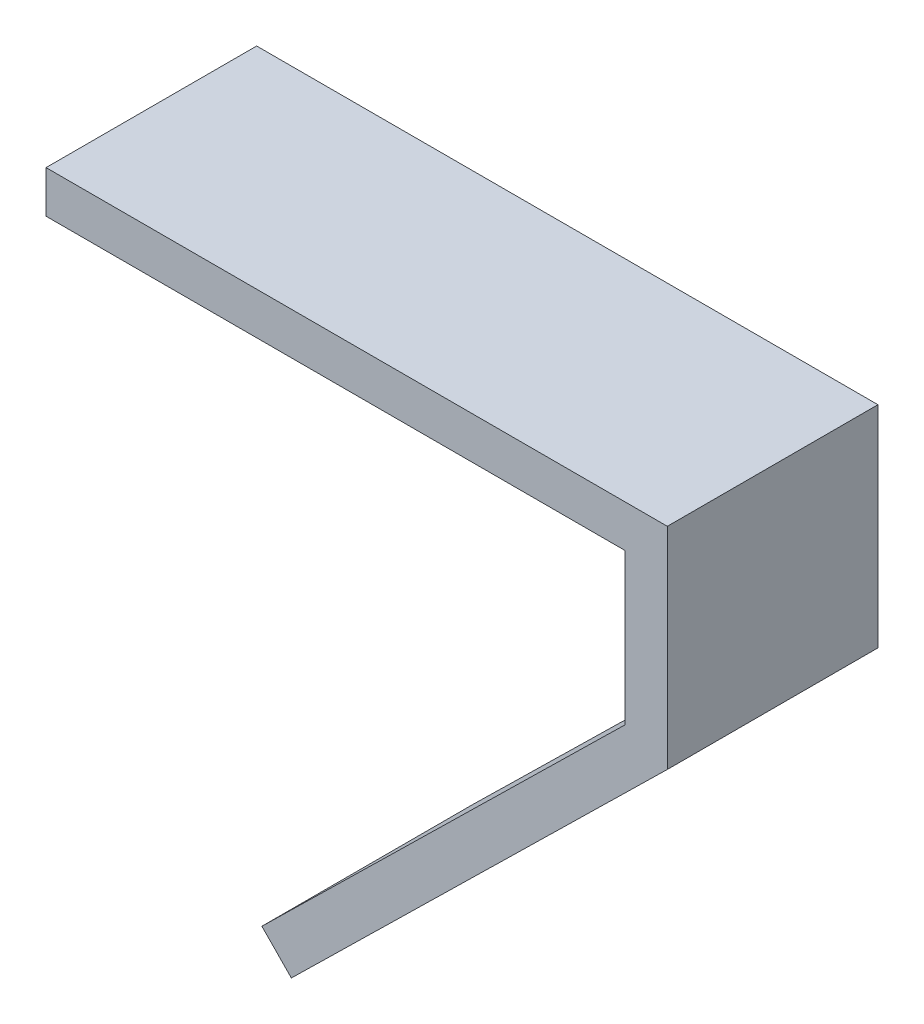
SolidWorks part; units mm, degrees
ref_plane "Front Plane" through (0, 0, 0) normal (0, 0, 1) x (1, 0, 0)
ref_plane "Top Plane" through (0, 0, 0) normal (0, 1, 0) x (1, 0, 0)
ref_plane "Right Plane" through (0, 0, 0) normal (1, 0, 0) x (0, 0, -1)
sketch "Sketch1" plane through (0, 0, 0) normal (0, 1, 0) x (1, 0, 0)
  line L0 (-86.6457, 0) -> (149.3256, 0) construction
  line L1 (-55, 0) -> (55, 0) construction
  line L2 (88.8579, 0) -> (88.8579, -74.8471) construction
ref_plane "Plane1" through (43.545, -44.4202, 0) normal (-0.7, 0.7141, 0) x (0, 0, 1)
sketch "Sketch2" plane through (43.545, -44.4202, 0) normal (-0.7, 0.7141, 0) x (0, 0, 1)
  line L1 (28.0347, 87.6783) -> (8.0347, 87.6783)
  line L2 (28.0347, 87.6783) -> (28.0347, 37.6783)
  line L3 (28.0347, 37.6783) -> (8.0347, 37.6783)
  line L4 (8.0347, 87.6783) -> (8.0347, 37.6783)
  line L5 (28.0347, 87.6783) -> (8.0347, 37.6783) construction
  line L6 (28.0347, 37.6783) -> (8.0347, 87.6783) construction
  point P0 (18.0347, 62.6783)
  dimension "D1" = 20
  dimension "D2" = 50
extrude "Boss-Extrude1" add sketch "Sketch2" along normal blind 4
sketch "Sketch3" plane through (0, 0, 28.0347) normal (0, 0, 1) x (1, 0, 0)
  line L1 (106.1566, 16.9579) -> (102.1566, 16.9579)
  line L2 (106.1566, 16.9579) -> (106.1566, 36.9579)
  line L3 (106.1566, 36.9579) -> (102.1566, 36.9579)
  line L4 (102.1566, 16.9579) -> (102.1566, 36.9579)
  dimension "D1" = 20
  dimension "D2" = 4
extrude "Boss-Extrude2" add sketch "Sketch3" against normal up to vertex (20 mm away)
sketch "Sketch4" plane through (102.1566, 0, 0) normal (-1, 0, 0) x (0, 0, 1)
  line L0 (28.0347, 36.9579) -> (28.0347, 18.6381) construction
  line L1 (8.0347, 36.9579) -> (28.0347, 36.9579)
  line L2 (8.0347, 36.9579) -> (8.0347, 32.9579)
  line L3 (8.0347, 32.9579) -> (28.0347, 32.9579)
  line L4 (28.0347, 36.9579) -> (28.0347, 32.9579)
  dimension "D1" = 4
extrude "Boss-Extrude3" add sketch "Sketch4" along normal blind 55
